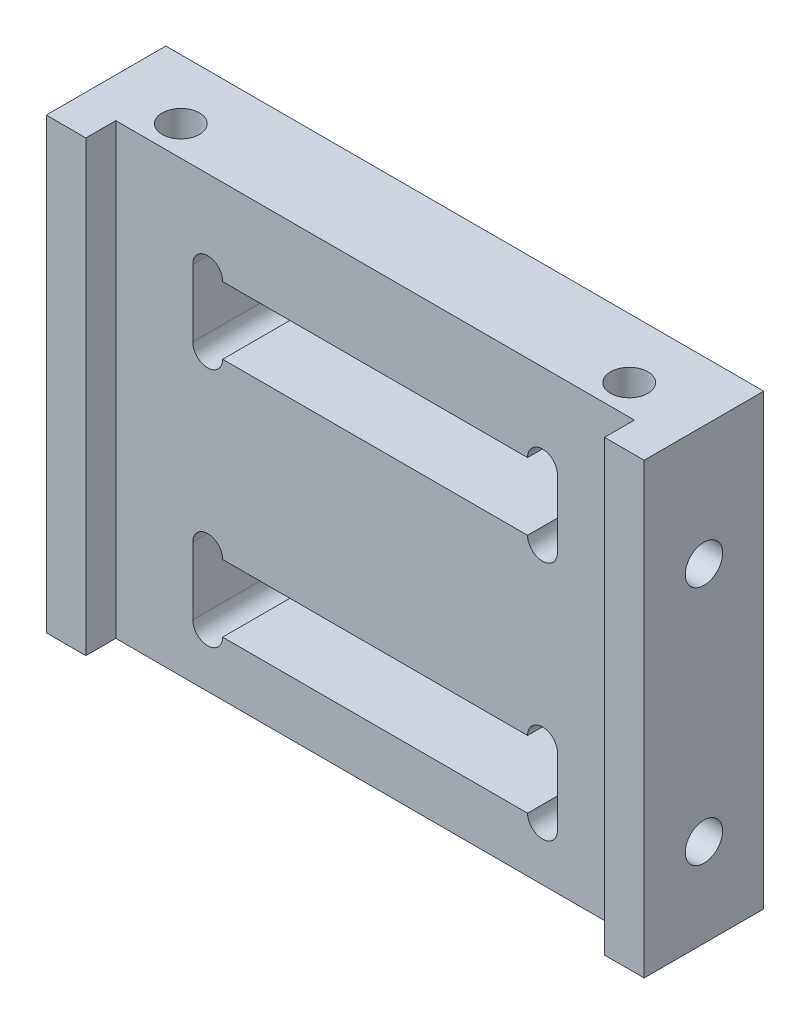
SolidWorks part; units mm, degrees
material "1.0503 (C45)"
ref_plane "Front Plane" through (0, 0, 0) normal (0, 0, 1) x (1, 0, 0)
ref_plane "Top Plane" through (0, 0, 0) normal (0, 1, 0) x (1, 0, 0)
ref_plane "Right Plane" through (0, 0, 0) normal (1, 0, 0) x (0, 0, -1)
sketch "Sketch1" plane through (0, 0, 0) normal (0, 0, 1) x (1, 0, 0)
  line L1 (20, -15) -> (-20, -15)
  line L2 (20, -15) -> (20, 15)
  line L3 (20, 15) -> (-20, 15)
  line L4 (-20, -15) -> (-20, 15)
  line L5 (20, -15) -> (-20, 15) construction
  line L6 (20, 15) -> (-20, -15) construction
  point P0 (0, 0)
  dimension "D1" = 30
  dimension "D2" = 40
extrude "Boss-Extrude1" add sketch "Sketch1" along normal mid plane 8
sketch "Sketch2" plane through (0, 0, 4) normal (0, 0, 1) x (1, 0, 0)
  line L0 (-11.65, -13.2) -> (-11.65, -15) construction
  line L1 (-20, -15) -> (20, -15) construction
  line L2 (-11.65, -15) -> (11.65, -15) construction
  line L3 (11.65, -15) -> (11.65, -13.2) construction
  line L4 (-11.65, -13.2) -> (-17.35, -13.2) construction
  line L5 (-17.35, -13.2) -> (-17.35, -3.15) construction
  line L6 (11.65, -13.2) -> (17.35, -13.2) construction
  line L7 (17.35, -13.2) -> (17.35, -3.15) construction
  line L8 (-15.85, -1.65) -> (15.85, -1.65) construction
  line L9 (0, -4.4) -> (0, 4.4) construction
  line L10 (-15.85, 21.25) -> (15.85, 21.25)
  line L11 (17.35, 19.75) -> (17.35, -5.75) construction
  line L12 (15.85, -7.25) -> (-15.85, -7.25) construction
  line L13 (-17.35, -5.75) -> (-17.35, 19.75) construction
  line L14 (-15.85, 19.75) -> (15.85, -5.75) construction
  line L15 (-15.85, -5.75) -> (15.85, 19.75) construction
  line L16 (-17.35, -13.2) -> (-17.35, -15)
  line L17 (-17.35, -15) -> (17.35, -15)
  line L18 (17.35, -15) -> (17.35, -13.2)
  line L19 (-17.35, -5.75) -> (-17.35, -3.15) construction
  line L20 (17.35, -3.15) -> (17.35, -5.75) construction
  line L21 (-17.35, 19.75) -> (-17.35, -13.2)
  line L22 (17.35, 19.75) -> (17.35, -13.2)
  arc A0 (-17.35, -3.15) -> (-15.85, -1.65) centre (-15.85, -3.15) cw construction
  arc A1 (17.35, -3.15) -> (15.85, -1.65) centre (15.85, -3.15) ccw construction
  arc A2 (15.85, 21.25) -> (17.35, 19.75) centre (15.85, 19.75) cw
  arc A3 (17.35, -5.75) -> (15.85, -7.25) centre (15.85, -5.75) cw construction
  arc A4 (-15.85, -7.25) -> (-17.35, -5.75) centre (-15.85, -5.75) cw construction
  arc A5 (-17.35, 19.75) -> (-15.85, 21.25) centre (-15.85, 19.75) cw
  point P14 (0, -1.65)
  point P17 (0, -15)
  point P21 (0, 21.25)
  point P33 (0, 7)
  dimension "D3" = 1.5
  dimension "D6" = 1.5
  dimension "D1" = 34.7
  dimension "D2" = 13.35
  dimension "D4" = 1.8
  dimension "D5" = 23.3
  dimension "D7" = 28.5
  dimension "D8" = 34.7
  dimension "D9" = 22
extrude "Cut-Extrude1" cut sketch "Sketch2" against normal blind 2
sketch "Sketch3" plane through (0, 0, 2) normal (0, 0, 1) x (1, 0, 0)
  line L0 (-12.2, 9.25) -> (-10.2, 9.25) construction
  line L1 (-10.2, -11.35) -> (10.2, -11.35) construction
  line L2 (-12.2, -11.35) -> (-12.2, -6.85) construction
  line L3 (-10.2, -6.85) -> (10.2, -6.85) construction
  line L4 (12.2, -11.35) -> (12.2, -6.85) construction
  line L5 (-12.2, -11.35) -> (12.2, -6.85) construction
  line L6 (-12.2, -6.85) -> (12.2, -11.35) construction
  line L7 (-10.2, 4.75) -> (10.2, 4.75) construction
  line L8 (-12.2, 4.75) -> (-12.2, 9.25) construction
  line L9 (-10.2, 9.25) -> (10.2, 9.25) construction
  line L10 (12.2, 4.75) -> (12.2, 9.25) construction
  line L11 (0, 7) -> (12.2, 9.25) construction
  line L12 (-12.2, 9.25) -> (0, 7) construction
  line L13 (0, -4.4) -> (0, 4.4) construction
  line L14 (12.2, 9.25) -> (12.2, 4.75)
  line L15 (10.2, 4.75) -> (-10.2, 4.75)
  line L16 (-12.2, 4.75) -> (-12.2, 9.25)
  line L17 (-10.2, 9.25) -> (10.2, 9.25)
  line L18 (-10.2, -6.85) -> (10.2, -6.85)
  line L19 (12.2, -6.85) -> (12.2, -11.35)
  line L20 (10.2, -11.35) -> (-10.2, -11.35)
  line L21 (-12.2, -11.35) -> (-12.2, -6.85)
  line L22 (-17.35, -15) -> (17.35, -15) construction
  line L23 (-12.2, 9.25) -> (-10.2, 9.25) construction
  line L24 (10.2, 9.25) -> (12.2, 9.25) construction
  line L25 (10.2, 9.25) -> (12.2, 9.25) construction
  line L26 (10.2, 4.75) -> (12.2, 4.75) construction
  line L27 (12.2, 4.75) -> (10.2, 4.75) construction
  line L28 (0, 7) -> (12.2, 4.75) construction
  line L29 (-12.2, 4.75) -> (-10.2, 4.75) construction
  line L30 (-10.2, 4.75) -> (-12.2, 4.75) construction
  line L31 (-12.2, 4.75) -> (0, 7) construction
  line L32 (-12.2, -6.85) -> (-10.2, -6.85) construction
  line L33 (-12.2, -6.85) -> (-10.2, -6.85) construction
  line L34 (-12.2, -11.35) -> (-10.2, -11.35) construction
  line L35 (-10.2, -11.35) -> (-12.2, -11.35) construction
  line L36 (10.2, -11.35) -> (12.2, -11.35) construction
  line L37 (12.2, -11.35) -> (10.2, -11.35) construction
  line L38 (10.2, -6.85) -> (12.2, -6.85) construction
  line L39 (10.2, -6.85) -> (12.2, -6.85) construction
  arc A0 (-12.2, 9.25) -> (-10.2, 9.25) centre (-11.2, 9.25) cw
  arc A1 (-12.2, 4.75) -> (-10.2, 4.75) centre (-11.2, 4.75) ccw
  arc A2 (12.2, 9.25) -> (10.2, 9.25) centre (11.2, 9.25) ccw
  arc A3 (10.2, 4.75) -> (12.2, 4.75) centre (11.2, 4.75) ccw
  arc A4 (-12.2, -6.85) -> (-10.2, -6.85) centre (-11.2, -6.85) cw
  arc A5 (-12.2, -11.35) -> (-10.2, -11.35) centre (-11.2, -11.35) ccw
  arc A6 (12.2, -6.85) -> (10.2, -6.85) centre (11.2, -6.85) ccw
  arc A7 (10.2, -11.35) -> (12.2, -11.35) centre (11.2, -11.35) ccw
  point P0 (0, -9.1)
  point P5 (0, 7)
  dimension "D5" = 1
  dimension "D6" = 1
  dimension "D7" = 1
  dimension "D8" = 1
  dimension "D9" = 1
  dimension "D10" = 1
  dimension "D11" = 1
  dimension "D2" = 4.5
  dimension "D4" = 24.4
  dimension "D1" = 22
  dimension "D3" = 5.9
extrude "Cut-Extrude2" cut sketch "Sketch3" against normal through all
hole_wizard "M3 Tapped Hole1" positions "Sketch11" profile "Sketch13" tap size "M3" standard "ISO"
sketch "Sketch11" plane through (-0.6622, -15, 0.5231) normal (0, 1, 0) x (1, 0, 0)
  line L0 (0.6622, -3.8769) -> (0.6622, 4.9231) construction
  line L1 (-15.8378, 0.5231) -> (17.1622, 0.5231) construction
  line L2 (0.6622, -3.8769) -> (0.6622, 4.9231) construction
  point P0 (15.1622, 0.5231)
  point P11 (-13.8378, 0.5231)
  dimension "D1" = 14.5
sketch "Sketch13" plane through (14.5, -15, 0) normal (1, 0, 0) x (0, 0, -1)
  line L0 (0, 0) -> (0, 9.7511)
  line L1 (0, 9.7511) -> (1.25, 9)
  line L2 (1.25, 9) -> (1.25, 0)
  line L5 (1.25, 0) -> (0, 0)
  line L10 (0, 9.7511) -> (-1.25, 9) construction
  line L11 (0, -6.35) -> (0, 107.95) construction
  dimension "Tap Drill Dia." = 2.5
  dimension "Tap Drill Depth" = 9
  dimension "Drill Angle" = 118
cosmetic thread "Hole Thread5" parameters "D1"=6, "D2"=3
cosmetic thread "Hole Thread6" parameters "D1"=6, "D2"=3
fillet "Fillet1" [suppressed] radius 1.05
fillet "Fillet2" [suppressed] radius 1.05
sketch "Sketch14" plane through (20, 0, 0) normal (1, 0, 0) x (0, 0, -1)
  line L0 (-9.5241, -9.95) -> (16.2989, -9.95) construction
  line L2 (-23.4122, 7) -> (17.0199, 7) construction
  point P3 (0, 7)
  point P6 (-2, -9.95)
  dimension "D1" = 5.05
  dimension "D2" = 16.95
  dimension "D3" = 2
hole_wizard "M3 Tapped Hole2" positions "Sketch15" profile "Sketch16" tap size "M3" standard "KS"
sketch "Sketch15" plane through (20, 0, 0) normal (1, 0, 0) x (0, 0, -1)
  line L0 (-2, 7) -> (6.6767, 7) construction
  line L2 (-14.0427, -9.1) -> (10.006, -9.1) construction
  line L3 (0, 0) -> (0, 12.8624) construction
  point P0 (0, 7)
  point P3 (0, -9.1)
sketch "Sketch16" plane through (20, 7, 0) normal (0, 1, 0) x (0, 0, -1)
  line L0 (0, 0) -> (0, 3.7511)
  line L1 (0, 3.7511) -> (1.25, 3)
  line L2 (1.25, 3) -> (1.25, 0)
  line L5 (1.25, 0) -> (0, 0)
  line L10 (0, 3.7511) -> (-1.25, 3) construction
  line L11 (0, -6.35) -> (0, 107.95) construction
  dimension "Tap Drill Dia." = 2.5
  dimension "Tap Drill Depth" = 3
  dimension "Drill Angle" = 118
cosmetic thread "Hole Thread1" [suppressed] parameters "D1"=6, "D2"=3
cosmetic thread "Hole Thread2" [suppressed] parameters "D1"=6, "D2"=3
cosmetic thread "Cosmetic Thread3" parameters "D1"=3, "D2"=3
cosmetic thread "Cosmetic Thread5" parameters "D1"=3, "D2"=3
mirror "Mirror1" about plane through (0, 0, 0) normal (1, 0, 0) of "M3 Tapped Hole2"
cosmetic thread "Hole Thread3" [suppressed] parameters "D1"=6, "D2"=3
cosmetic thread "Hole Thread4" [suppressed] parameters "D1"=6, "D2"=3
cosmetic thread "Cosmetic Thread4" parameters "D1"=3, "D2"=3
cosmetic thread "Cosmetic Thread6" parameters "D1"=3, "D2"=3
hole_wizard "Tap Drill for M3 Tap1" positions "Sketch17" profile "Sketch18" hole size "M3" standard "ISO"
sketch "Sketch17" plane through (0, 15, 0) normal (0, 1, 0) x (1, 0, 0)
  line L0 (0, -4.4) -> (0, 4.4) construction
  line L2 (-16.5, 0) -> (16.5, 0) construction
  point P0 (-15, 0)
  point P2 (15, 0)
  dimension "D1" = 15
  dimension "D2" = 30
sketch "Sketch18" plane through (-15, 15, 0) normal (1, 0, 0) x (0, 0, 1)
  line L0 (0, 0) -> (0, 5.2511)
  line L1 (0, 5.2511) -> (1.25, 4.5)
  line L2 (1.25, 4.5) -> (1.25, 0)
  line L5 (1.25, 0) -> (0, 0)
  line L10 (0, 5.2511) -> (-1.25, 4.5) construction
  line L11 (0, -6.35) -> (0, 107.95) construction
  dimension "Hole Dia." = 2.5
  dimension "Hole Depth" = 4.5
  dimension "Drill Angle" = 118
cosmetic thread "Cosmetic Thread1" parameters "D2"=3
cosmetic thread "Cosmetic Thread2" parameters "D2"=3
sketch "Sketch19" [suppressed] plane through (0, 0, -4) normal (0, 0, -1) x (-1, 0, 0)
  line L0 (20, -16) -> (14.5, -16)
  line L1 (20, -16.5) -> (-20, -16.5) construction
  line L2 (14.5, -16) -> (14.5, -9)
  line L3 (-20, -16) -> (-14.5, -16)
  line L4 (12, -10.5) -> (17, -10.5)
  line L5 (12, -10.5) -> (12, -7.5)
  line L6 (12, -7.5) -> (17, -7.5)
  line L7 (17, -10.5) -> (17, -7.5)
  line L8 (12, -10.5) -> (17, -7.5) construction
  line L9 (12, -7.5) -> (17, -10.5) construction
  line L10 (-14.5, -16) -> (-14.5, -9)
  line L12 (-17, -10.5) -> (-12, -10.5)
  line L13 (-17, -10.5) -> (-17, -7.5)
  line L14 (-17, -7.5) -> (-12, -7.5)
  line L15 (-12, -10.5) -> (-12, -7.5)
  line L16 (-17, -10.5) -> (-12, -7.5) construction
  line L17 (-17, -7.5) -> (-12, -10.5) construction
  dimension "D1" = 3
  dimension "D2" = 5
  dimension "D3" = 3
  dimension "D4" = 5
equation "\"Radius\"=1.5"
equation "\"D6@Sketch2\"=\"Radius\""
equation "\"D3@Sketch2\"=\"Radius\""
equation "\"Height_core\"= 14.9"
equation "\"D7@Sketch2\"=\"Height_core\" + 3.6+10"
equation "\"D2@Sketch2\" = \"Height_core\" - 1.55"
equation "\"Width_core\"= 34.4 + 0.3"
equation "\"D8@Sketch2\" = \"Width_core\""
equation "\"D1@Sketch2\" = \"Width_core\""
equation "\"Width_Holder\"= 40"
equation "\"D2@Sketch1\"=\"Width_Holder\""
equation "\"Height_Holder\"=30"
equation "\"D1@Sketch1\"=\"Height_Holder\""
equation "\"Height_Kicker\"=22"
equation "\"D9@Sketch2\"=\"Height_Kicker\""
equation "\"Height_core_hole\"=4.5"
equation "\"D2@Sketch3\"=\"Height_core_hole\""
equation "\"Width_core_hole\"=24.4"
equation "\"D4@Sketch3\"=\"Width_core_hole\""
equation "\"D1@Sketch3\"= \"Height_Kicker\""
equation "\"D3@Sketch3\"=\"Height_core\"/2-1.55"
equation "\"D1@Sketch11\" = \"Width_Holder\" / 2 - 5.5"
equation "\"D2@Sketch17\"=\"D1@Sketch17\"*2"
